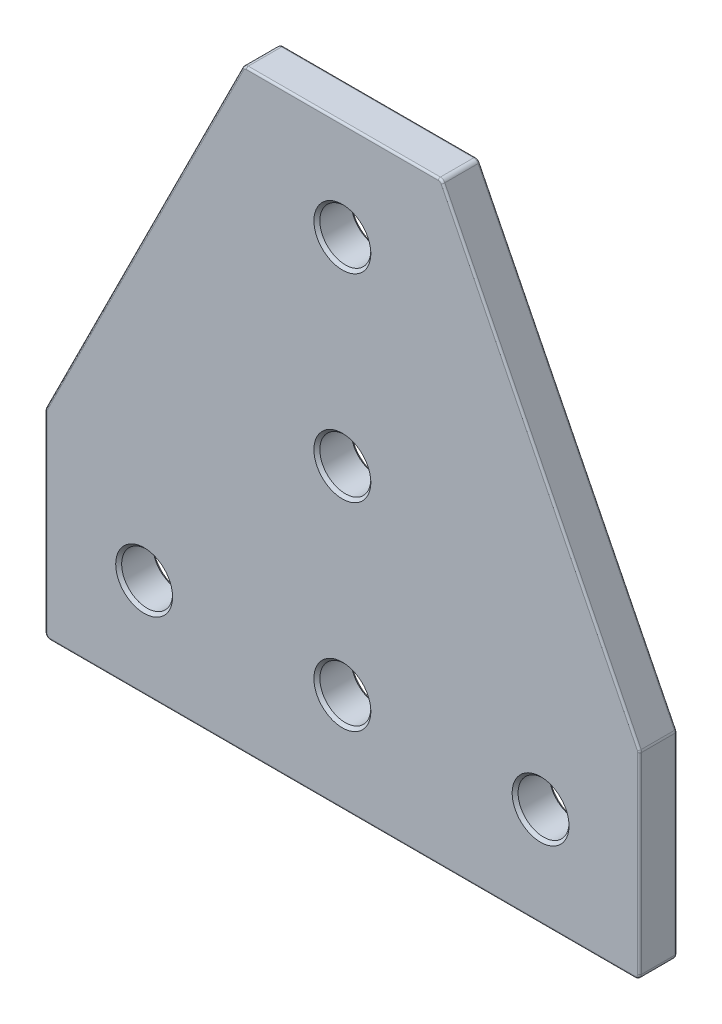
SolidWorks part; units mm, degrees
ref_plane "Front Plane" through (0, 0, 0) normal (0, 0, 1) x (1, 0, 0)
ref_plane "Top Plane" through (0, 0, 0) normal (0, 1, 0) x (1, 0, 0)
ref_plane "Right Plane" through (0, 0, 0) normal (1, 0, 0) x (0, 0, -1)
sketch "Sketch1" plane through (0, 0, 0) normal (0, 0, 1) x (1, 0, 0)
  line L0 (0, 38.1) -> (0, -38.1) construction
  line L1 (-38.1, -38.1) -> (38.1, -38.1) construction
  line L2 (-12.7, 38.1) -> (12.7, 38.1) construction
  line L3 (-38.1, -38.1) -> (-38.1, -12.7) construction
  line L4 (-38.1, -12.7) -> (-12.7, 38.1) construction
  line L5 (12.7, 38.1) -> (38.1, -12.7) construction
  line L6 (38.1, -12.7) -> (38.1, -38.1) construction
  line L7 (-25.4, -25.4) -> (0, -25.4) construction
  line L8 (-28.575, -25.4) -> (-27.305, -25.4) construction
  circle A0 centre (-25.4, -25.4) radius 3.2639
  circle A1 centre (-25.4, -25.4) radius 3.175 construction
  dimension "Mounting Hole Diameter" = 6.5278
  dimension "Mounting Fastener Thread Size" = 6.35
  dimension "Length" = 76.2
  dimension "Top Flat" = 25.4
  dimension "Side Flat" = 25.4
  dimension "Mounting Hole Offset" = 12.7
  dimension "Mounting Hole CtoC" = 25.4
  dimension "D3" = 12.7
  dimension "Mounting Fastener Thread Pitch" = 1.27
sketch "Sketch2" plane through (0, 0, 0) normal (1, 0, 0) x (0, 0, -1)
  line L0 (-2.3876, -25.4) -> (2.3876, -25.4) construction
  line L1 (2.3876, -25.4) -> (10.3124, -25.4) construction
  dimension "Thickness" = 4.7752
  dimension "Mounting Fastener Thread Length" = 12.7
sketch "Sketch3" plane through (0, 0, 0) normal (0, 0, 1) x (1, 0, 0)
  line L0 (-38.1, -38.1) -> (-38.1, -12.7) construction
  line L1 (-38.1, -38.1) -> (38.1, -38.1) construction
  line L2 (38.1, -12.7) -> (38.1, -38.1) construction
  line L3 (12.7, 38.1) -> (38.1, -12.7) construction
  line L4 (-12.7, 38.1) -> (12.7, 38.1) construction
  line L5 (-38.1, -12.7) -> (-12.7, 38.1) construction
  line L6 (-38.1, -38.1) -> (-38.1, -12.7)
  line L7 (-38.1, -38.1) -> (38.1, -38.1)
  line L8 (38.1, -12.7) -> (38.1, -38.1)
  line L9 (12.7, 38.1) -> (38.1, -12.7)
  line L10 (-12.7, 38.1) -> (12.7, 38.1)
  line L11 (-38.1, -12.7) -> (-12.7, 38.1)
extrude "Boss-Extrude1" add sketch "Sketch3" along normal up to vertex (2.3876 mm away) from vertex at -2.3876 starting at point (0, -25.4, -2.3876)
sketch "Sketch4" plane through (0, 0, 2.3876) normal (0, 0, 1) x (1, 0, 0)
  circle A0 centre (-25.4, -25.4) radius 3.2639 construction
  circle A1 centre (-25.4, -25.4) radius 3.2639
extrude "Cut-Extrude1" cut sketch "Sketch4" against normal through all
chamfer "Chamfer1" distance 0.381 angle 45 2 edges at (-22.1361, -25.4, 2.3876) (-22.1361, -25.4, -2.3876)
pattern_linear "LPattern1" count 3 spacing 25.4 along (1, 0, 0) count 3 spacing 25.4 along (0, 1, 0) skipping (0, 1), (0, 2), (2, 1), (2, 2) of "Cut-Extrude1", "Chamfer1"
fillet "Fillet1" radius 0.635 6 edges at (-38.1, -38.1, 0) (-38.1, -12.7, 0) (-12.7, 38.1, 0) (12.7, 38.1, 0) (38.1, -38.1, 0) (38.1, -12.7, 0)
fillet "Fillet2" radius 0.254 24 edges at (38.083, -12.704, 2.3876) (38.1, -25.1575, 2.3876) (37.914, -37.914, 2.3876) (0, -38.1, 2.3876) (-37.914, -37.914, 2.3876) (-38.1, -25.1575, 2.3876) (-38.083, -12.704, 2.3876) (-25.4542, 12.5915, 2.3876) (-12.6414, 38.0052, 2.3876) (0, 38.1, 2.3876) (12.6414, 38.0052, 2.3876) (38.083, -12.704, -2.3876) (38.1, -25.1575, -2.3876) (37.914, -37.914, -2.3876) (0, -38.1, -2.3876) (-37.914, -37.914, -2.3876) (-38.1, -25.1575, -2.3876) (-38.083, -12.704, -2.3876) (-25.4542, 12.5915, -2.3876) (-12.6414, 38.0052, -2.3876) (0, 38.1, -2.3876) (12.6414, 38.0052, -2.3876) (25.4542, 12.5915, 2.3876) (25.4542, 12.5915, -2.3876)
equation "\"D3@Sketch1\" = \"Mounting Hole Offset@Sketch1\""
equation "\"D4@LPattern1\"=\"D3@LPattern1\""
equation "\"D3@LPattern1\"=\"Mounting Hole CtoC@Sketch1\""
